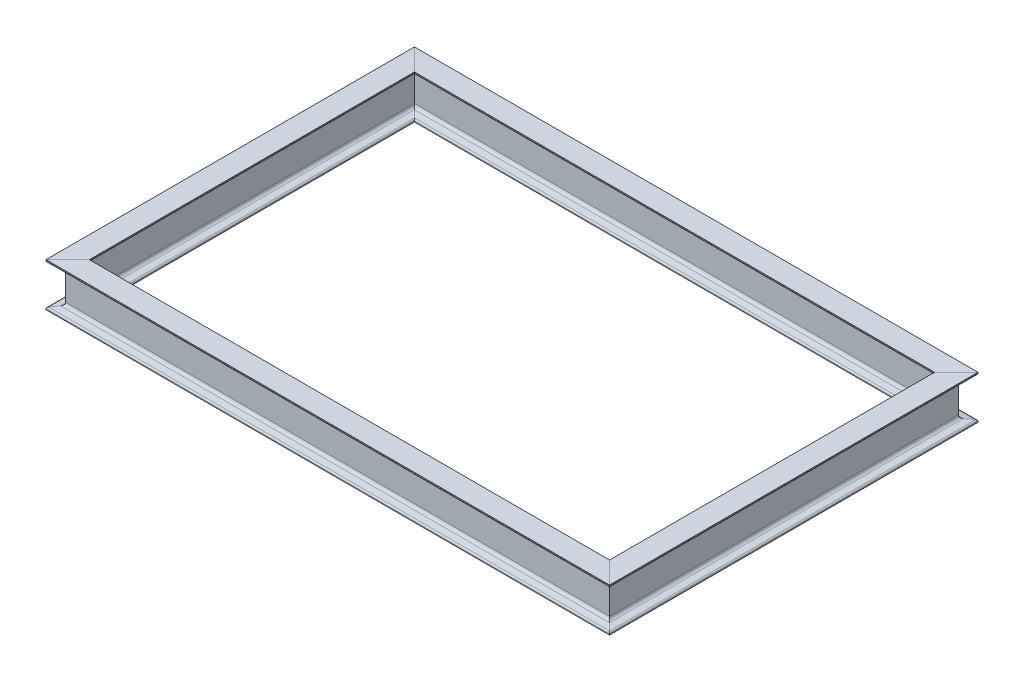
SolidWorks part; units mm, degrees
other "SB BEAM 100 x 8 x 800 (A)"
other "SB BEAM 100 x 8 x 1250 (A)"
other "SB BEAM 100 x 8 x 800 (B)"
other "SB BEAM 100 x 8 x 1250 (B)"
ref_plane "Front" through (0, 0, 0) normal (0, 0, 1) x (1, 0, 0)
ref_plane "Top" through (0, 0, 0) normal (0, 1, 0) x (1, 0, 0)
ref_plane "Right" through (0, 0, 0) normal (1, 0, 0) x (0, 0, -1)
sketch "Sketch1" plane through (0, 0, 0) normal (0, 1, 0) x (1, 0, 0)
  line L1 (-625, 400) -> (625, 400)
  line L2 (-625, 400) -> (-625, -400)
  line L3 (-625, -400) -> (625, -400)
  line L4 (625, 400) -> (625, -400)
  point P4 (0, 400)
  point P6 (-625, 0)
  dimension "D1" = 800
  dimension "D2" = 1250
other "Sb beam 100 X 8(1)"
ref_plane "Plane1" through (-625, 0, -400) normal (0, 0, 1) x (1, 0, 0)
sketch "Sketch11" plane through (-625, 0, -400) normal (0, 0, 1) x (1, 0, 0)
  line L0 (-25, -50) -> (-25, -48.0607)
  line L1 (-22.0754, -44.6083) -> (-8.0991, -42.2787)
  line L2 (-2.25, -35.374) -> (-2.25, 35.374)
  line L3 (-8.0991, 42.2787) -> (-22.0754, 44.6083)
  line L4 (-25, 48.0607) -> (-25, 50)
  line L5 (-25, 50) -> (25, 50)
  line L6 (25, 50) -> (25, 48.0607)
  line L7 (22.0754, 44.6083) -> (8.0991, 42.2787)
  line L8 (2.25, 35.374) -> (2.25, -35.374)
  line L9 (8.0991, -42.2787) -> (22.0754, -44.6083)
  line L10 (25, -48.0607) -> (25, -50)
  line L11 (25, -50) -> (-25, -50)
  line L15 (-2.25, 0) -> (2.25, 0) construction
  arc A0 (-8.0991, -42.2787) -> (-2.25, -35.374) centre (-9.25, -35.374) ccw
  arc A1 (-2.25, 35.374) -> (-8.0991, 42.2787) centre (-9.25, 35.374) ccw
  arc A2 (8.0991, 42.2787) -> (2.25, 35.374) centre (9.25, 35.374) ccw
  arc A3 (2.25, -35.374) -> (8.0991, -42.2787) centre (9.25, -35.374) ccw
  arc A4 (-22.0754, 44.6083) -> (-25, 48.0607) centre (-21.5, 48.0607) cw
  arc A5 (22.0754, 44.6083) -> (25, 48.0607) centre (21.5, 48.0607) ccw
  arc A6 (-25, -48.0607) -> (-22.0754, -44.6083) centre (-21.5, -48.0607) cw
  arc A7 (25, -48.0607) -> (22.0754, -44.6083) centre (21.5, -48.0607) ccw
  point P1 (0, 50)
  point P8 (0, -50)
  point P21 (0, 0)
  point P34 (0, 0)
  dimension "RI" = 7
  dimension "D3" = 3.5
  dimension "BF" = 50
  dimension "D2" = 9.463
  dimension "DEPTH" = 100
  dimension "TW" = 4.5
  dimension "D1" = 70.748
delete or keep bodies "Body-Delete/Keep 1(Config_0)" [suppressed] type delete bodies bodies 102 104 101
delete or keep bodies "Body-Delete/Keep 1(Config_1)" [suppressed] type delete bodies bodies 102 104 103
delete or keep bodies "Body-Delete/Keep 1(Config_2)" [suppressed] type delete bodies bodies 102 101 103
delete or keep bodies "Body-Delete/Keep 1(Config_3)" [suppressed] type delete bodies bodies 104 101 103
